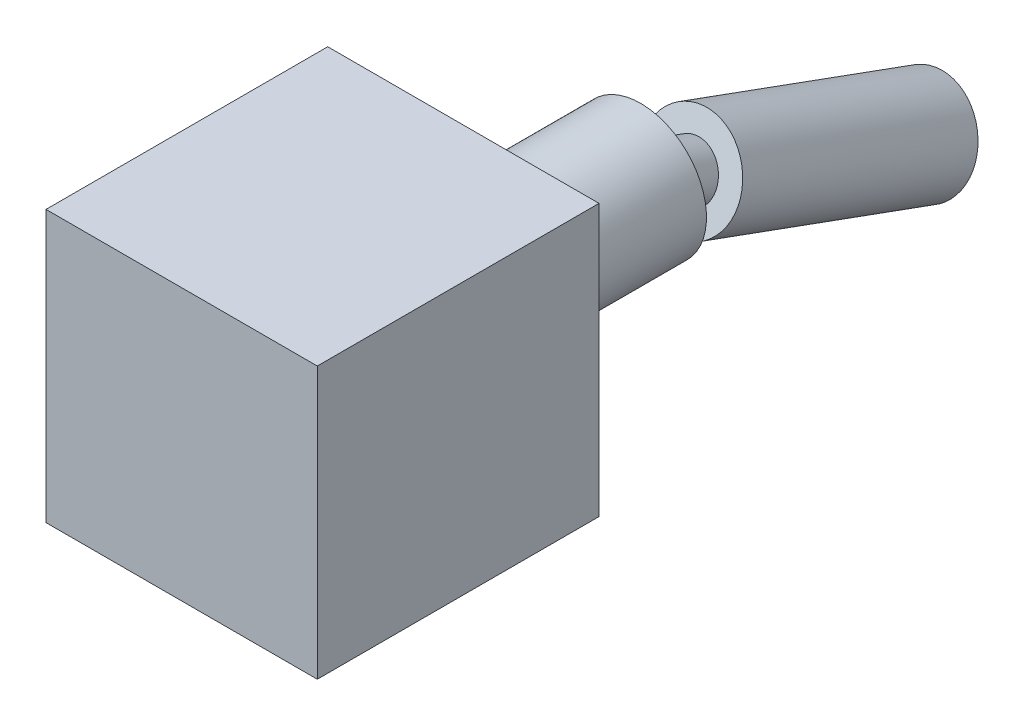
SolidWorks part; units mm, degrees
material "Chrome Stainless Steel"
ref_plane "Front Plane" through (0, 0, 0) normal (0, 0, 1) x (1, 0, 0)
ref_plane "Top Plane" through (0, 0, 0) normal (0, 1, 0) x (1, 0, 0)
ref_plane "Right Plane" through (0, 0, 0) normal (1, 0, 0) x (0, 0, -1)
sketch "Sketch1" plane through (0, 0, 0) normal (0, 1, 0) x (1, 0, 0)
  line L1 (-6.5, -6.75) -> (6.5, -6.75)
  line L2 (-6.5, -6.75) -> (-6.5, 6.75)
  line L3 (-6.5, 6.75) -> (6.5, 6.75)
  line L4 (6.5, -6.75) -> (6.5, 6.75)
  line L5 (-6.5, -6.75) -> (6.5, 6.75) construction
  line L6 (-6.5, 6.75) -> (6.5, -6.75) construction
  point P0 (0, 0)
  dimension "D1" = 13
  dimension "D2" = 13.5
extrude "Boss-Extrude1" add sketch "Sketch1" along normal blind 13
sketch "Sketch2" plane through (0, 0, -6.75) normal (0, 0, -1) x (-1, 0, 0)
  line L0 (-6.5, 6.5) -> (0, 6.5) construction
  line L1 (-6.5, 13) -> (-6.5, 0) construction
  line L2 (0, 6.5) -> (0, 0) construction
  circle A0 centre (0, 6.5) radius 3.15
  dimension "D1" = 6.3
extrude "Boss-Extrude2" add sketch "Sketch2" along normal blind 8.5
sketch "Sketch3" plane through (0, 0, -6.75) normal (0, 0, -1) x (-1, 0, 0)
  circle A0 centre (0, 6.5) radius 4
  dimension "D1" = 8
extrude "Boss-Extrude3" add sketch "Sketch3" along normal blind 1
sketch "Sketch4" plane through (0, 0, 0) normal (1, 0, 0) x (0, 0, -1)
  line L0 (15.25, 6.5) -> (23.9702, 6.5) construction
  line L1 (15.25, 3.35) -> (15.25, 9.65) construction
  line L2 (15.25, 6.5) -> (24.4013, 3.1692) construction
  line L3 (14.3103, 6.842) -> (13.8657, 5.6204)
  line L4 (13.8657, 5.6204) -> (17.1546, 4.4233)
  line L5 (17.1546, 4.4233) -> (16.7784, 3.3897)
  line L6 (16.7784, 3.3897) -> (28.2426, -0.783)
  line L7 (28.2426, -0.783) -> (28.636, 0.2977)
  line L8 (29.6939, 1.2429) -> (30.9277, 4.6329) construction
  line L9 (14.3103, 6.842) -> (29.6939, 1.2429)
  arc A0 (28.636, 0.2977) -> (29.6939, 1.2429) centre (28.2843, 1.7559) ccw
  dimension "D7" = 2.5
  dimension "D8" = 1.5
  dimension "D1" = 20
  dimension "D2" = 3.5
  dimension "D3" = 1.3
  dimension "D4" = 2.4
  dimension "D5" = 1
  dimension "D6" = 12.2
revolve "Revolve1" add sketch "Sketch4" angle 360 about L2
chamfer "Chamfer1" distance 0.2 angle 45 1 edges at (0, -0.783, -28.2426)
